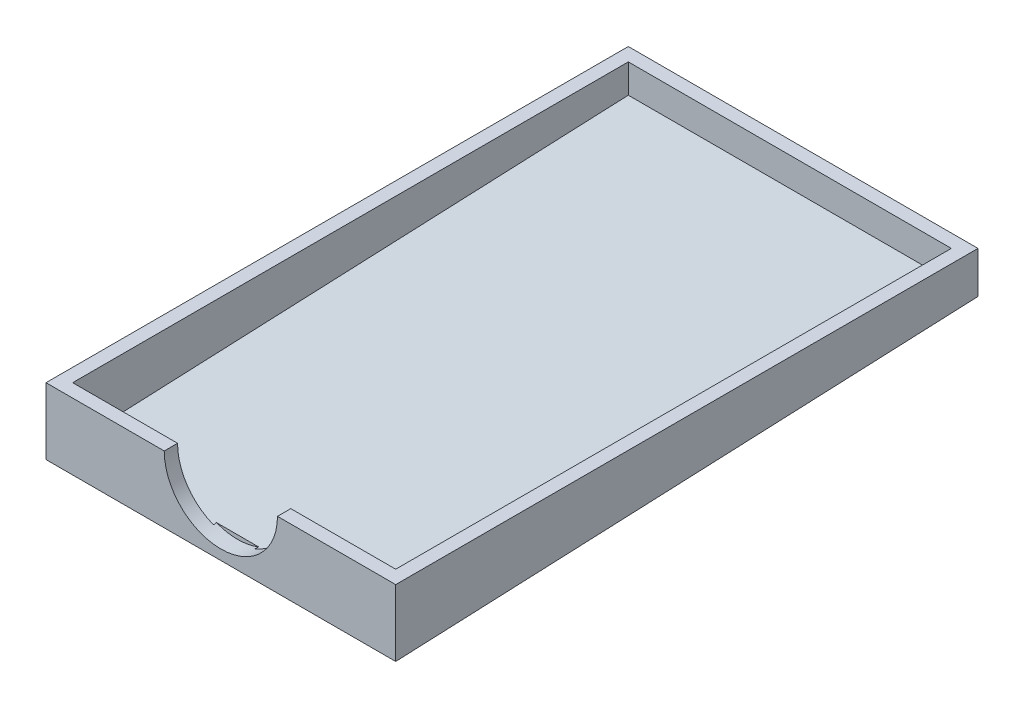
SolidWorks part; units mm, degrees
ref_plane "Front Plane" through (0, 0, 0) normal (0, 0, 1) x (1, 0, 0)
ref_plane "Top Plane" through (0, 0, 0) normal (0, 1, 0) x (1, 0, 0)
ref_plane "Right Plane" through (0, 0, 0) normal (1, 0, 0) x (0, 0, -1)
sketch "Sketch1" plane through (0, 0, 0) normal (1, 0, 0) x (0, 0, -1)
  line L0 (-34.9678, -1.5) -> (34.9678, 1.5)
  line L1 (-34.9678, -1.5) -> (-34.9678, 6.5)
  line L2 (-34.9678, 6.5) -> (34.9678, 6.5)
  line L3 (34.9678, 6.5) -> (34.9678, 1.5)
  dimension "D1" = 70
  dimension "D2" = 8
  dimension "D3" = 5
extrude "Boss-Extrude1" add sketch "Sketch1" along normal mid plane 42
shell "Shell1" thickness 1.6
sketch "Sketch2" plane through (0, 0, 34.9678) normal (0, 0, 1) x (1, 0, 0)
  line L0 (21, 6.5) -> (-21, 6.5) construction
  circle A0 centre (0, 6.5) radius 6.8
  dimension "D1" = 13.6
extrude "Cut-Extrude1" cut sketch "Sketch2" against normal blind 2
